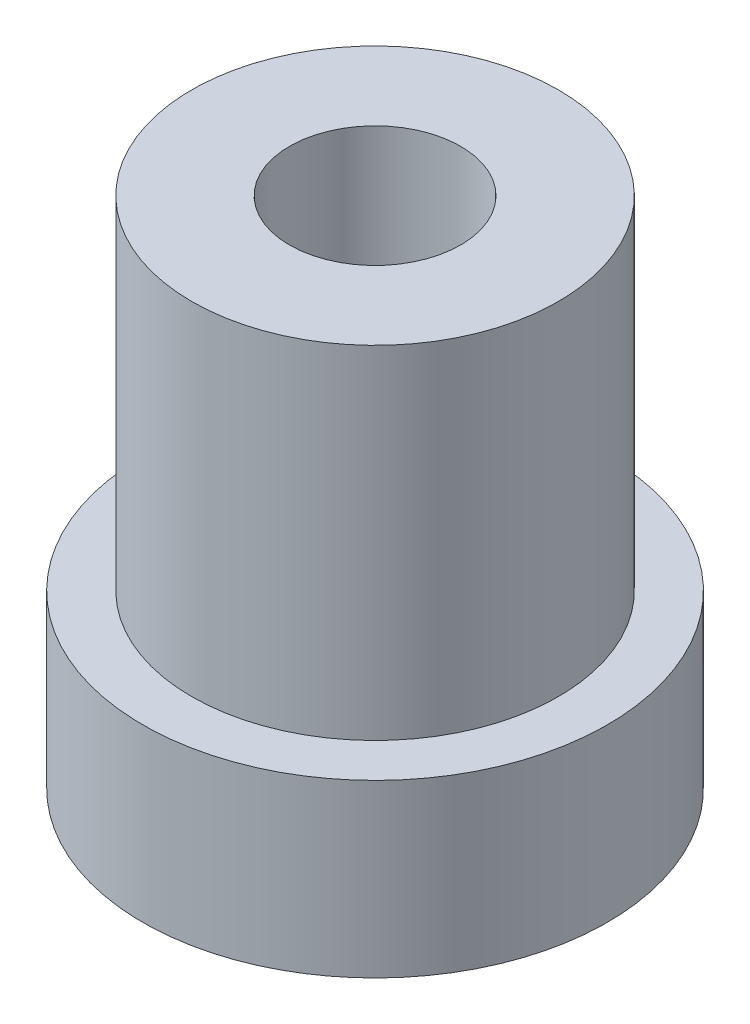
SolidWorks part; units mm, degrees
ref_plane "Front Plane" through (0, 0, 0) normal (0, 0, 1) x (1, 0, 0)
ref_plane "Top Plane" through (0, 0, 0) normal (0, 1, 0) x (1, 0, 0)
ref_plane "Right Plane" through (0, 0, 0) normal (1, 0, 0) x (0, 0, -1)
sketch "Sketch1" plane through (0, 0, 0) normal (0, 1, 0) x (1, 0, 0)
  circle A0 centre (0, 0) radius 3.75
  dimension "D1" = 7.5
extrude "Boss-Extrude1" add sketch "Sketch1" along normal blind 10.5
hole_wizard "Ø3.5 (3.5) Diameter Hole1" positions "Sketch2" profile "Sketch3" hole size "Ø3.5" standard "JIS" end condition through all
sketch "Sketch2" plane through (0, 10.5, 0) normal (0, 1, 0) x (1, 0, 0)
  point P0 (0, 0)
sketch "Sketch3" plane through (0, 10.5, 0) normal (1, 0, 0) x (0, 0, 1)
  line L0 (0, 0) -> (0, 10.5)
  line L1 (0, 10.5) -> (1.75, 10.5)
  line L2 (1.75, 10.5) -> (1.75, 0)
  line L5 (1.75, 0) -> (0, 0)
  line L11 (0, -6.35) -> (0, 107.95) construction
  dimension "Thru Hole Dia." = 3.5
  dimension "Thru Hole Depth" = 10.5
sketch "Sketch5" plane through (0, 0, 0) normal (0, -1, 0) x (1, 0, 0)
  circle A0 centre (0, 0) radius 3.75 construction
  circle A1 centre (0, 0) radius 3.75
  circle A2 centre (0, 0) radius 4.75
  dimension "D1" = 9.5
extrude "Boss-Extrude2" add sketch "Sketch5" against normal blind 3.5
